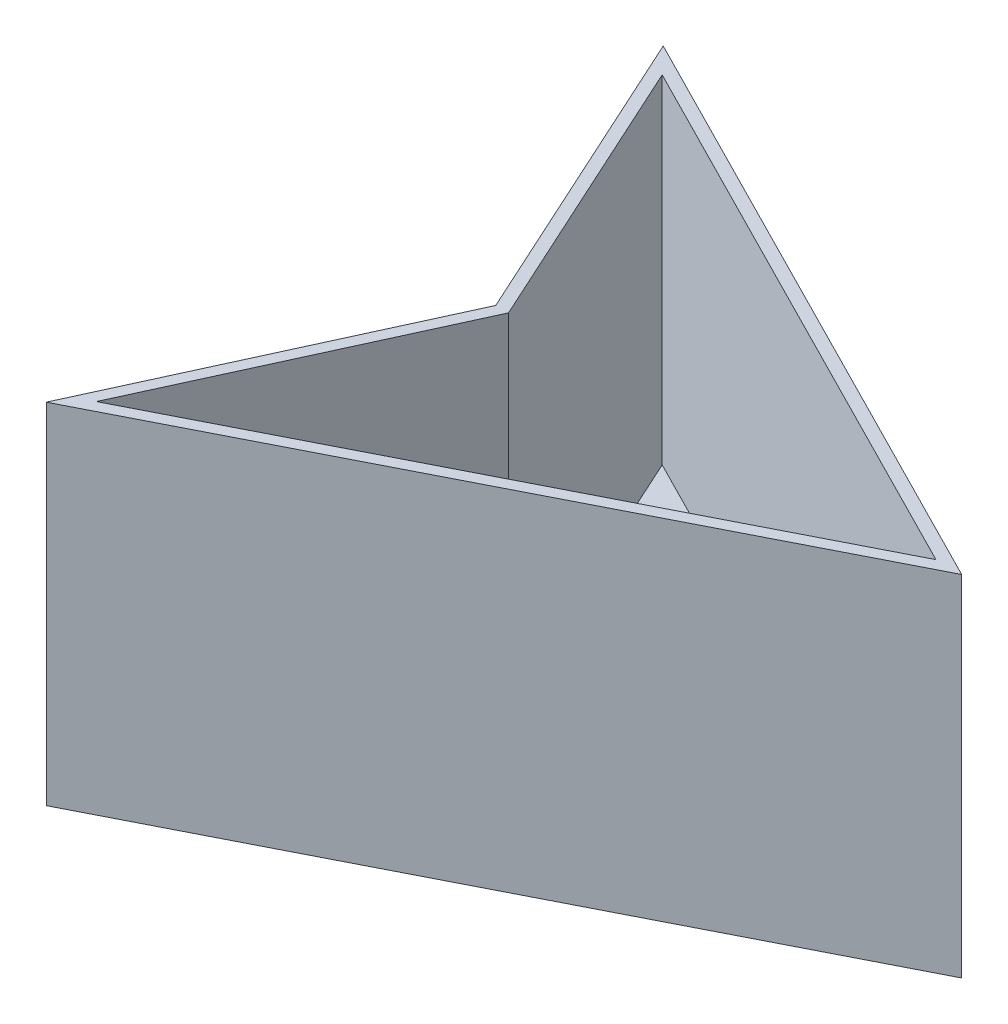
SolidWorks part; units mm, degrees
ref_plane "Alzado" through (0, 0, 0) normal (0, 0, 1) x (1, 0, 0)
ref_plane "Planta" through (0, 0, 0) normal (0, 1, 0) x (1, 0, 0)
ref_plane "Vista lateral" through (0, 0, 0) normal (1, 0, 0) x (0, 0, -1)
sketch "Croquis2" plane through (0, 0, 0) normal (0, 1, 0) x (1, 0, 0)
  line L0 (2.7471, -570.0977) -> (52.4543, -570.0977) construction
  line L1 (0, 0) -> (20, 0) construction
  line L2 (20, 0) -> (-6.05, 13.2393)
  line L3 (-6.05, 13.2393) -> (0, 0)
  line L4 (20, 0) -> (-6.05, -13.2393)
  line L5 (-6.05, -13.2393) -> (0, 0)
  circle A0 centre (6, 0) radius 5.5 construction
  dimension "D2" = 11
  dimension "D3" = 14
  dimension "D1" = 20
  dimension "D4" = 38.5
  dimension "D5" = 6.05
extrude "Saliente-Extruir1" add sketch "Croquis2" along normal blind 15
shell "Vaciado1" thickness 0.5
